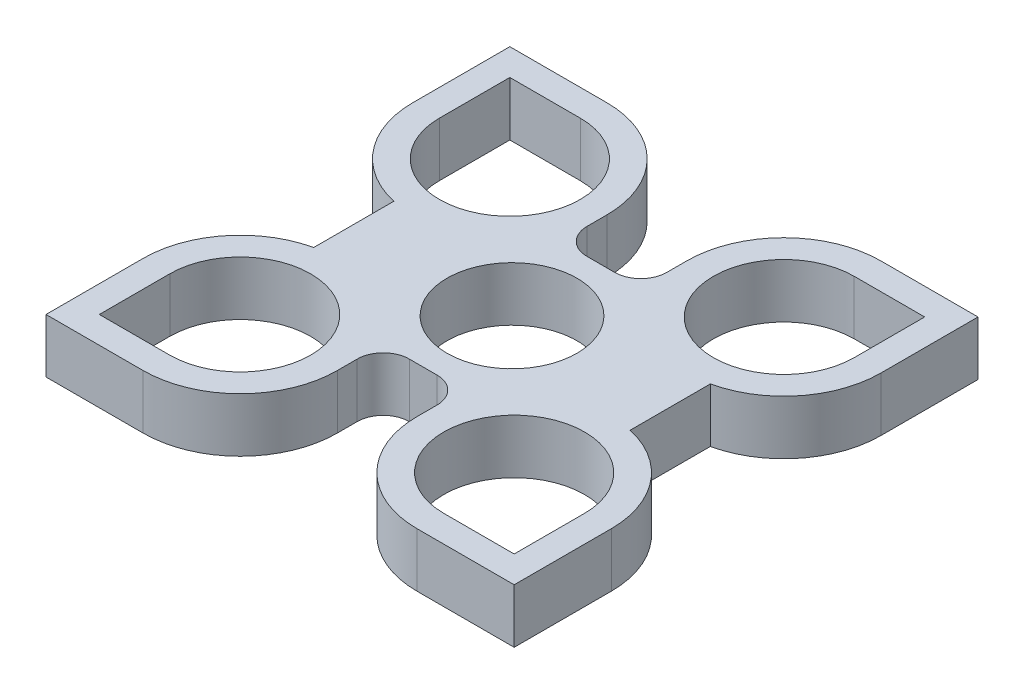
SolidWorks part; units mm, degrees
ref_plane "Front Plane" through (0, 0, 0) normal (0, 0, 1) x (1, 0, 0)
ref_plane "Top Plane" through (0, 0, 0) normal (0, 1, 0) x (1, 0, 0)
ref_plane "Right Plane" through (0, 0, 0) normal (1, 0, 0) x (0, 0, -1)
sketch "Sketch1" plane through (0, 0, 0) normal (0, 1, 0) x (1, 0, 0)
  line L0 (0, 125.9834) -> (0, -133.8545) construction
  line L1 (-108, 107) -> (-63.2, 107)
  line L2 (-108, 107) -> (-108, 62.2)
  line L3 (-108, -107) -> (-63.2, -107)
  line L4 (108, 107) -> (108, 62.2)
  line L5 (-108, 62.2) -> (-95.7, 62.2) construction
  line L6 (-108, -107) -> (108, 107) construction
  line L7 (-123.7708, 0) -> (123.7708, 0) construction
  line L8 (-63.2, 107) -> (-63.2, 94.7) construction
  line L9 (-63.2, 94.7) -> (-95.7, 94.7)
  line L10 (-95.7, 62.2) -> (-95.7, 94.7)
  line L11 (-73, 18.485) -> (-73, -18.485)
  line L12 (73, 18.485) -> (73, -18.485)
  line L13 (-63.2, -94.7) -> (-95.7, -94.7)
  line L14 (-95.7, -62.2) -> (-95.7, -94.7)
  line L15 (63.2, -94.7) -> (95.7, -94.7)
  line L16 (95.7, -62.2) -> (95.7, -94.7)
  line L17 (63.2, 94.7) -> (95.7, 94.7)
  line L18 (95.7, 62.2) -> (95.7, 94.7)
  line L19 (108, -62.2) -> (108, -107)
  line L20 (-108, -62.2) -> (-108, -107)
  line L21 (-63.2, 62.2) -> (63.2, 62.2) construction
  line L22 (63.2, 62.2) -> (63.2, -62.2) construction
  line L23 (63.2, -62.2) -> (-63.2, -62.2) construction
  line L24 (-63.2, -62.2) -> (-63.2, 62.2) construction
  line L25 (-18.4, 62.2) -> (-18.4, 53)
  line L26 (18.4, 62.2) -> (18.4, 53)
  line L27 (-18.4, -62.2) -> (-18.4, -53)
  line L28 (18.4, -62.2) -> (18.4, -53)
  line L29 (0, -41) -> (-6.4, -41)
  line L30 (0, -41) -> (6.4, -41)
  line L31 (0, 41) -> (6.4, 41)
  line L32 (0, 41) -> (-6.4, 41)
  line L33 (63.2, -107) -> (108, -107)
  line L34 (63.2, 107) -> (108, 107)
  circle A0 centre (0, 0) radius 30
  arc A1 (-95.7, 62.2) -> (-63.2, 94.7) centre (-63.2, 62.2) ccw
  arc A2 (-108, 62.2) -> (-73, 18.485) centre (-63.2, 62.2) ccw
  arc A3 (-95.7, -62.2) -> (-63.2, -94.7) centre (-63.2, -62.2) cw
  arc A4 (-108, -62.2) -> (-73, -18.485) centre (-63.2, -62.2) cw
  arc A5 (95.7, -62.2) -> (63.2, -94.7) centre (63.2, -62.2) ccw
  arc A6 (108, -62.2) -> (73, -18.485) centre (63.2, -62.2) ccw
  arc A7 (95.7, 62.2) -> (63.2, 94.7) centre (63.2, 62.2) cw
  arc A8 (108, 62.2) -> (73, 18.485) centre (63.2, 62.2) cw
  arc A9 (-18.4, -62.2) -> (-63.2, -107) centre (-63.2, -62.2) cw
  arc A11 (18.4, -53) -> (6.4, -41) centre (6.4, -53) ccw
  arc A12 (-6.4, -41) -> (-18.4, -53) centre (-6.4, -53) ccw
  arc A13 (18.4, 53) -> (6.4, 41) centre (6.4, 53) cw
  arc A14 (-6.4, 41) -> (-18.4, 53) centre (-6.4, 53) cw
  arc A15 (18.4, -62.2) -> (63.2, -107) centre (63.2, -62.2) ccw
  arc A16 (-18.4, 62.2) -> (-63.2, 107) centre (-63.2, 62.2) ccw
  arc A17 (18.4, 62.2) -> (63.2, 107) centre (63.2, 62.2) cw
  point P0 (0, 0)
  dimension "D3" = 146
  dimension "D4" = 12
  dimension "D1" = 216
  dimension "D2" = 214
extrude "Boss-Extrude1" add sketch "Sketch1" along normal blind 25
